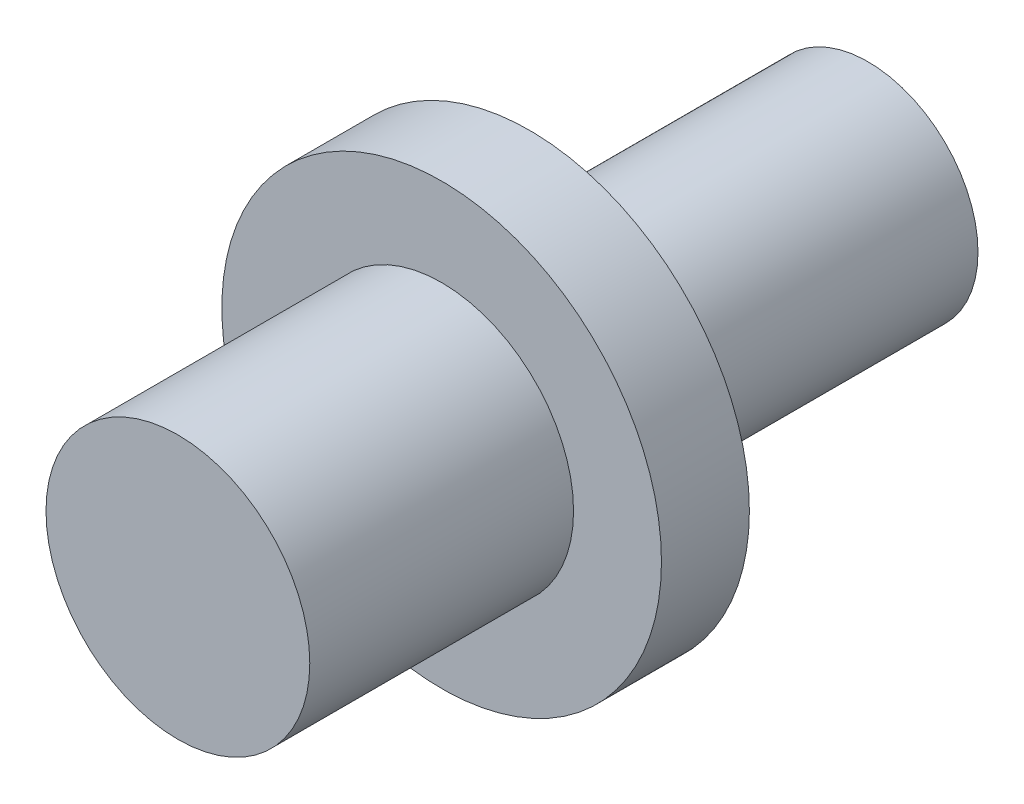
SolidWorks part; units mm, degrees
ref_plane "Piano frontale" through (0, 0, 0) normal (0, 0, 1) x (1, 0, 0)
ref_plane "Piano superiore" through (0, 0, 0) normal (0, 1, 0) x (1, 0, 0)
ref_plane "Piano destro" through (0, 0, 0) normal (1, 0, 0) x (0, 0, -1)
sketch "Schizzo2" plane through (0, 0, 0) normal (1, 0, 0) x (0, 0, -1)
  line L0 (0, 0) -> (0, 3)
  line L1 (0, 3) -> (6, 3)
  line L2 (6, 3) -> (6, 5)
  line L3 (6, 5) -> (8, 5)
  line L4 (8, 5) -> (8, 2.5)
  line L5 (8, 2.5) -> (13, 2.5)
  line L6 (0, 0) -> (19.0571, 0) construction
  line L7 (13, 2.5) -> (15.7, 2.5)
  line L8 (15.7, 2.5) -> (15.7, 0)
  line L9 (0, 0) -> (15.7, 0)
  dimension "D1" = 2
  dimension "D2" = 5
  dimension "D3" = 6
  dimension "D4" = 3
  dimension "D5" = 5
  dimension "D6" = 2.5
  dimension "D7" = 2.7
revolve "Rivoluzione1" add sketch "Schizzo2" angle 360 about L6
